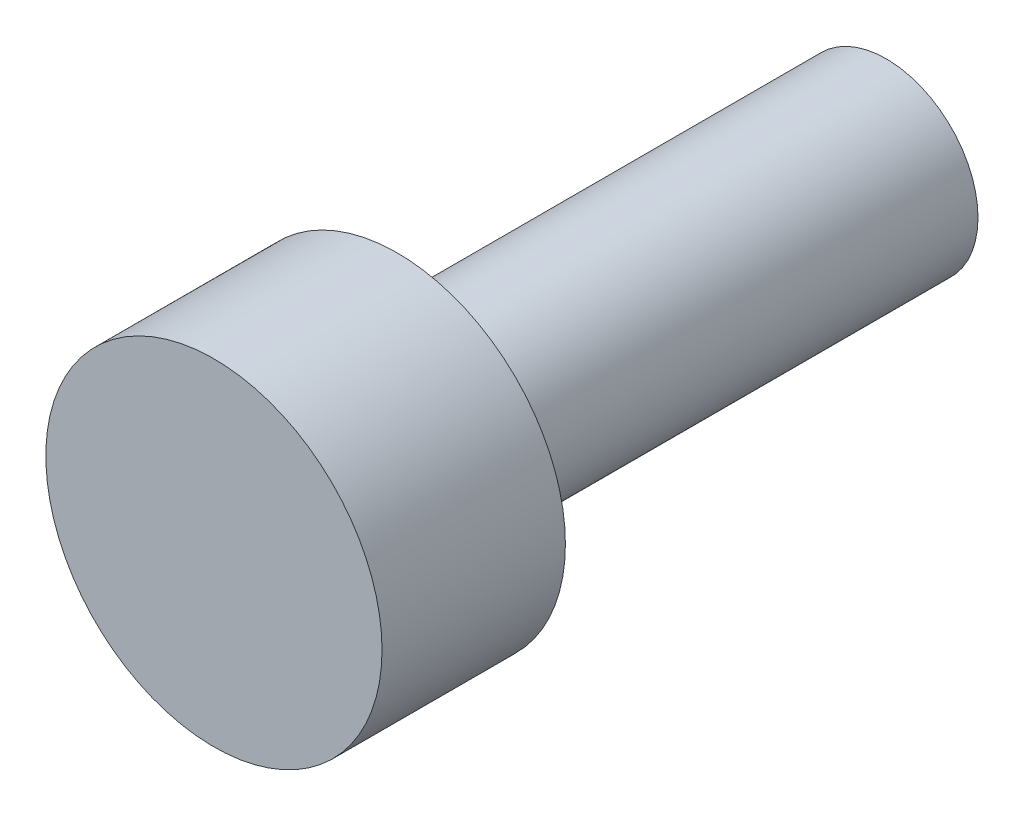
SolidWorks part; units mm, degrees
ref_plane "前视基准面" through (0, 0, 0) normal (0, 0, 1) x (1, 0, 0)
ref_plane "上视基准面" through (0, 0, 0) normal (0, 1, 0) x (1, 0, 0)
ref_plane "右视基准面" through (0, 0, 0) normal (1, 0, 0) x (0, 0, -1)
other "Configuration Table"
sketch "Sketch_Nominal_shank" plane through (0, 0, 0) normal (0, 0, 1) x (1, 0, 0)
  circle A0 centre (0, 0) radius 1.5
  dimension "D1" = 3
extrude "Nominal_shank" add sketch "Sketch_Nominal_shank" along normal blind 8 from offset 8
sketch "Sketch_Head" plane through (0, 0, 0) normal (0, 0, 1) x (1, 0, 0)
  circle A0 centre (0, 0) radius 2.75
  dimension "D1" = 5.5
extrude "Head" add sketch "Sketch_Head" along normal blind 3 from offset 0
